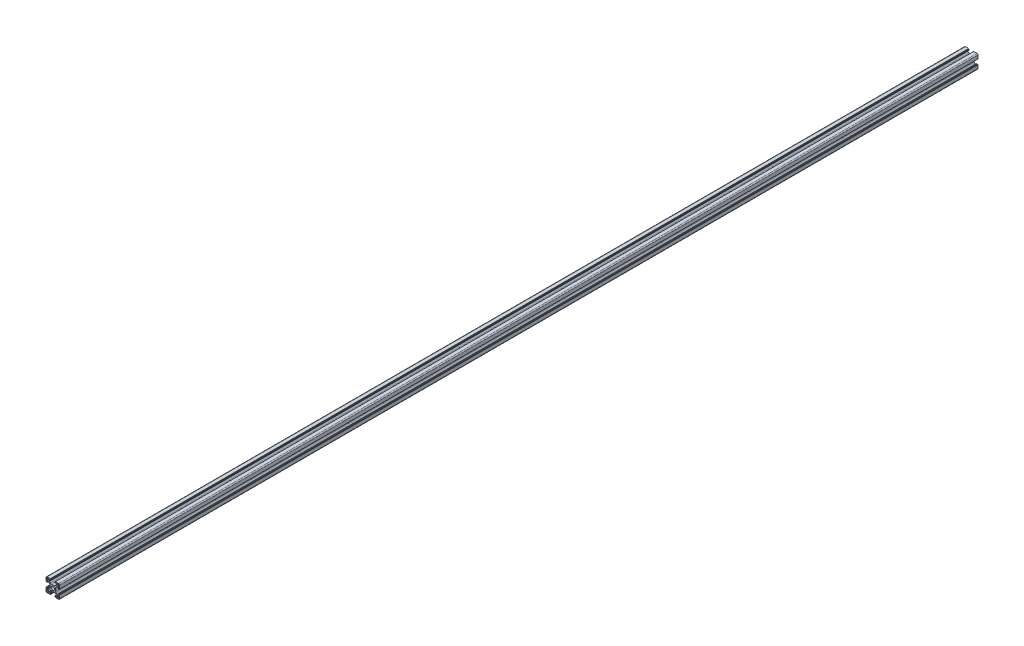
SolidWorks part; units mm, degrees
ref_plane "Спереди" through (0, 0, 0) normal (0, 0, 1) x (1, 0, 0)
ref_plane "Сверху" through (0, 0, 0) normal (0, 1, 0) x (1, 0, 0)
ref_plane "Справа" through (0, 0, 0) normal (1, 0, 0) x (0, 0, -1)
sketch "Эскиз1" plane through (0, 0, 0) normal (0, 0, 1) x (1, 0, 0)
  line L0 (-25.8933, 69.2728) -> (-28.8933, 66.2728) construction
  line L1 (-34.9933, 64.1728) -> (-33.0945, 64.1728)
  line L2 (-34.9933, 60.1728) -> (-24.9933, 70.1728) construction
  line L3 (-27.3933, 67.7728) -> (-28.8933, 69.2728) construction
  line L4 (-31.6803, 64.7586) -> (-30.3791, 66.0598)
  line L5 (-28.0933, 66.2728) -> (-26.6933, 66.2728)
  line L6 (-28.8933, 67.0728) -> (-28.8933, 68.4728)
  line L7 (-26.6933, 69.2728) -> (-28.0933, 69.2728)
  line L8 (-29.7933, 68.3728) -> (-29.7933, 67.474)
  line L9 (-31.2301, 68.246) -> (-30.7498, 68.7264)
  line L10 (-31.7933, 69.7219) -> (-31.2933, 69.7219)
  line L11 (-31.4069, 68.1728) -> (-31.6933, 68.1728)
  line L12 (-30.3962, 68.8728) -> (-30.2933, 68.8728)
  line L13 (-31.2933, 70.0228) -> (-31.2933, 69.7219)
  line L14 (-31.9433, 69.5719) -> (-31.9433, 68.4228)
  line L15 (-26.4933, 70.1728) -> (-31.1433, 70.1728)
  line L16 (-25.8933, 68.4728) -> (-25.8933, 67.0728)
  line L17 (-24.9933, 68.6728) -> (-24.9933, 64.0228)
  line L18 (-25.5943, 63.2228) -> (-26.7433, 63.2228)
  line L19 (-25.1433, 63.8728) -> (-25.4443, 63.8728)
  line L20 (-26.2933, 64.7699) -> (-26.2933, 64.8728)
  line L21 (-26.9933, 63.7592) -> (-26.9933, 63.4728)
  line L22 (-25.4443, 63.3728) -> (-25.4443, 63.8728)
  line L23 (-26.9201, 63.936) -> (-26.4398, 64.4164)
  line L24 (-26.7933, 65.3728) -> (-27.6921, 65.3728)
  line L25 (-30.4075, 63.4858) -> (-29.1063, 64.787)
  line L26 (-30.9933, 60.1728) -> (-30.9933, 62.0716)
  line L27 (-30.9933, 60.1728) -> (-30.9933, 58.274)
  line L28 (-30.4075, 56.8598) -> (-29.1063, 55.5586)
  line L29 (-28.8933, 53.2728) -> (-28.8933, 51.8728)
  line L30 (-28.0933, 54.0728) -> (-26.6933, 54.0728)
  line L31 (-25.8933, 51.8728) -> (-25.8933, 53.2728)
  line L32 (-26.7933, 54.9728) -> (-27.6921, 54.9728)
  line L33 (-26.9201, 56.4096) -> (-26.4398, 55.9292)
  line L34 (-25.4443, 56.9728) -> (-25.4443, 56.4728)
  line L35 (-26.9933, 56.5864) -> (-26.9933, 56.8728)
  line L36 (-26.2933, 55.5757) -> (-26.2933, 55.4728)
  line L37 (-25.1433, 56.4728) -> (-25.4443, 56.4728)
  line L38 (-25.5943, 57.1228) -> (-26.7433, 57.1228)
  line L39 (-24.9933, 51.6728) -> (-24.9933, 56.3228)
  line L40 (-26.6933, 51.0728) -> (-28.0933, 51.0728)
  line L41 (-26.4933, 50.1728) -> (-31.1433, 50.1728)
  line L42 (-31.9433, 50.7737) -> (-31.9433, 51.9228)
  line L43 (-31.2933, 50.3228) -> (-31.2933, 50.6237)
  line L44 (-30.3962, 51.4728) -> (-30.2933, 51.4728)
  line L45 (-31.4069, 52.1728) -> (-31.6933, 52.1728)
  line L46 (-31.7933, 50.6237) -> (-31.2933, 50.6237)
  line L47 (-31.2301, 52.0996) -> (-30.7498, 51.6192)
  line L48 (-29.7933, 51.9728) -> (-29.7933, 52.8716)
  line L49 (-31.6803, 55.587) -> (-30.3791, 54.2858)
  line L50 (-34.9933, 56.1728) -> (-33.0945, 56.1728)
  line L51 (-25.8933, 51.0728) -> (-28.8933, 54.0728) construction
  line L52 (-34.9933, 60.1728) -> (-24.9933, 50.1728) construction
  line L53 (-27.3933, 52.5728) -> (-25.8933, 54.0728) construction
  line L54 (-34.9933, 56.1728) -> (-36.8921, 56.1728)
  line L55 (-38.3063, 55.587) -> (-39.6075, 54.2858)
  line L56 (-41.8933, 54.0728) -> (-43.2933, 54.0728)
  line L57 (-41.0933, 53.2728) -> (-41.0933, 51.8728)
  line L58 (-43.2933, 51.0728) -> (-41.8933, 51.0728)
  line L59 (-40.1933, 51.9728) -> (-40.1933, 52.8716)
  line L60 (-38.7565, 52.0996) -> (-39.2369, 51.6192)
  line L61 (-38.1933, 50.6237) -> (-38.6933, 50.6237)
  line L62 (-38.5798, 52.1728) -> (-38.2933, 52.1728)
  line L63 (-39.5904, 51.4728) -> (-39.6933, 51.4728)
  line L64 (-38.6933, 50.3228) -> (-38.6933, 50.6237)
  line L65 (-38.0433, 50.7737) -> (-38.0433, 51.9228)
  line L66 (-43.4933, 50.1728) -> (-38.8433, 50.1728)
  line L67 (-44.0933, 51.8728) -> (-44.0933, 53.2728)
  line L68 (-44.9933, 51.6728) -> (-44.9933, 56.3228)
  line L69 (-44.3924, 57.1228) -> (-43.2433, 57.1228)
  line L70 (-44.8433, 56.4728) -> (-44.5424, 56.4728)
  line L71 (-43.6933, 55.5757) -> (-43.6933, 55.4728)
  line L72 (-42.9933, 56.5864) -> (-42.9933, 56.8728)
  line L73 (-44.5424, 56.9728) -> (-44.5424, 56.4728)
  line L74 (-43.0665, 56.4096) -> (-43.5469, 55.9292)
  line L75 (-43.1933, 54.9728) -> (-42.2945, 54.9728)
  line L76 (-39.5791, 56.8598) -> (-40.8803, 55.5586)
  line L77 (-38.9933, 60.1728) -> (-38.9933, 58.274)
  line L78 (-44.0933, 51.0728) -> (-41.0933, 54.0728) construction
  line L79 (-34.9933, 60.1728) -> (-44.9933, 50.1728) construction
  line L80 (-42.5933, 52.5728) -> (-41.0933, 51.0728) construction
  line L81 (-38.9933, 60.1728) -> (-38.9933, 62.0716)
  line L82 (-39.5791, 63.4858) -> (-40.8803, 64.787)
  line L83 (-41.0933, 67.0728) -> (-41.0933, 68.4728)
  line L84 (-41.8933, 66.2728) -> (-43.2933, 66.2728)
  line L85 (-44.0933, 68.4728) -> (-44.0933, 67.0728)
  line L86 (-43.1933, 65.3728) -> (-42.2945, 65.3728)
  line L87 (-43.0665, 63.936) -> (-43.5469, 64.4164)
  line L88 (-44.5424, 63.3728) -> (-44.5424, 63.8728)
  line L89 (-42.9933, 63.7592) -> (-42.9933, 63.4728)
  line L90 (-43.6933, 64.7699) -> (-43.6933, 64.8728)
  line L91 (-44.8433, 63.8728) -> (-44.5424, 63.8728)
  line L92 (-44.3924, 63.2228) -> (-43.2433, 63.2228)
  line L93 (-44.9933, 68.6728) -> (-44.9933, 64.0228)
  line L94 (-43.2933, 69.2728) -> (-41.8933, 69.2728)
  line L95 (-43.4933, 70.1728) -> (-38.8433, 70.1728)
  line L96 (-38.0433, 69.5719) -> (-38.0433, 68.4228)
  line L97 (-38.6933, 70.0228) -> (-38.6933, 69.7219)
  line L98 (-39.5904, 68.8728) -> (-39.6933, 68.8728)
  line L99 (-38.5798, 68.1728) -> (-38.2933, 68.1728)
  line L100 (-38.1933, 69.7219) -> (-38.6933, 69.7219)
  line L101 (-38.7565, 68.246) -> (-39.2369, 68.7264)
  line L102 (-40.1933, 68.3728) -> (-40.1933, 67.474)
  line L103 (-38.3063, 64.7586) -> (-39.6075, 66.0598)
  line L104 (-34.9933, 64.1728) -> (-36.8921, 64.1728)
  line L105 (-46.7574, 60.1728) -> (-23.489, 60.1728) construction
  line L106 (-44.0933, 69.2728) -> (-41.0933, 66.2728) construction
  line L107 (-34.9933, 48.0864) -> (-34.9933, 70.8917) construction
  line L108 (-34.9933, 60.1728) -> (-44.9933, 70.1728) construction
  line L109 (-42.5933, 67.7728) -> (-44.0933, 66.2728) construction
  arc A0 (-25.8933, 68.4728) -> (-26.6933, 69.2728) centre (-26.6933, 68.4728) ccw
  arc A1 (-28.0933, 69.2728) -> (-28.8933, 68.4728) centre (-28.0933, 68.4728) ccw
  arc A2 (-28.0933, 66.2728) -> (-28.8933, 67.0728) centre (-28.0933, 67.0728) cw
  arc A3 (-26.4933, 70.1728) -> (-24.9933, 68.6728) centre (-26.4933, 68.6728) cw
  arc A4 (-31.7933, 69.7219) -> (-31.9433, 69.5719) centre (-31.7933, 69.5719) ccw
  arc A5 (-31.1433, 70.1728) -> (-31.2933, 70.0228) centre (-31.1433, 70.0228) ccw
  arc A6 (-31.4069, 68.1728) -> (-31.2301, 68.246) centre (-31.4069, 68.4228) ccw
  arc A7 (-31.6933, 68.1728) -> (-31.9433, 68.4228) centre (-31.6933, 68.4228) cw
  arc A8 (-30.7498, 68.7264) -> (-30.3962, 68.8728) centre (-30.3962, 68.3728) cw
  arc A9 (-30.2933, 68.8728) -> (-29.7933, 68.3728) centre (-30.2933, 68.3728) cw
  arc A10 (-32.4933, 60.1728) -> (-34.9933, 62.6728) centre (-34.9933, 60.1728) ccw
  arc A11 (-33.0945, 64.1728) -> (-31.6803, 64.7586) centre (-33.0945, 66.1728) ccw
  arc A12 (-29.7933, 67.474) -> (-30.3791, 66.0598) centre (-31.7933, 67.474) cw
  arc A13 (-25.8933, 67.0728) -> (-26.6933, 66.2728) centre (-26.6933, 67.0728) cw
  arc A14 (-26.2933, 64.8728) -> (-26.7933, 65.3728) centre (-26.7933, 64.8728) ccw
  arc A15 (-26.4398, 64.4164) -> (-26.2933, 64.7699) centre (-26.7933, 64.7699) ccw
  arc A16 (-26.9933, 63.4728) -> (-26.7433, 63.2228) centre (-26.7433, 63.4728) ccw
  arc A17 (-26.9933, 63.7592) -> (-26.9201, 63.936) centre (-26.7433, 63.7592) cw
  arc A18 (-24.9933, 64.0228) -> (-25.1433, 63.8728) centre (-25.1433, 64.0228) cw
  arc A19 (-25.4443, 63.3728) -> (-25.5943, 63.2228) centre (-25.5943, 63.3728) cw
  arc A20 (-27.6921, 65.3728) -> (-29.1063, 64.787) centre (-27.6921, 63.3728) ccw
  arc A21 (-30.9933, 62.0716) -> (-30.4075, 63.4858) centre (-28.9933, 62.0716) cw
  arc A22 (-26.6933, 51.0728) -> (-25.8933, 51.8728) centre (-26.6933, 51.8728) ccw
  arc A23 (-25.8933, 53.2728) -> (-26.6933, 54.0728) centre (-26.6933, 53.2728) ccw
  arc A24 (-28.8933, 53.2728) -> (-28.0933, 54.0728) centre (-28.0933, 53.2728) cw
  arc A25 (-24.9933, 51.6728) -> (-26.4933, 50.1728) centre (-26.4933, 51.6728) cw
  arc A26 (-25.4443, 56.9728) -> (-25.5943, 57.1228) centre (-25.5943, 56.9728) ccw
  arc A27 (-24.9933, 56.3228) -> (-25.1433, 56.4728) centre (-25.1433, 56.3228) ccw
  arc A28 (-26.9933, 56.5864) -> (-26.9201, 56.4096) centre (-26.7433, 56.5864) ccw
  arc A29 (-26.9933, 56.8728) -> (-26.7433, 57.1228) centre (-26.7433, 56.8728) cw
  arc A30 (-26.4398, 55.9292) -> (-26.2933, 55.5757) centre (-26.7933, 55.5757) cw
  arc A31 (-26.2933, 55.4728) -> (-26.7933, 54.9728) centre (-26.7933, 55.4728) cw
  arc A32 (-34.9933, 57.6728) -> (-32.4933, 60.1728) centre (-34.9933, 60.1728) ccw
  arc A33 (-30.9933, 58.274) -> (-30.4075, 56.8598) centre (-28.9933, 58.274) ccw
  arc A34 (-27.6921, 54.9728) -> (-29.1063, 55.5586) centre (-27.6921, 56.9728) cw
  arc A35 (-28.0933, 51.0728) -> (-28.8933, 51.8728) centre (-28.0933, 51.8728) cw
  arc A36 (-30.2933, 51.4728) -> (-29.7933, 51.9728) centre (-30.2933, 51.9728) ccw
  arc A37 (-30.7498, 51.6192) -> (-30.3962, 51.4728) centre (-30.3962, 51.9728) ccw
  arc A38 (-31.6933, 52.1728) -> (-31.9433, 51.9228) centre (-31.6933, 51.9228) ccw
  arc A39 (-31.4069, 52.1728) -> (-31.2301, 52.0996) centre (-31.4069, 51.9228) cw
  arc A40 (-31.1433, 50.1728) -> (-31.2933, 50.3228) centre (-31.1433, 50.3228) cw
  arc A41 (-31.7933, 50.6237) -> (-31.9433, 50.7737) centre (-31.7933, 50.7737) cw
  arc A42 (-29.7933, 52.8716) -> (-30.3791, 54.2858) centre (-31.7933, 52.8716) ccw
  arc A43 (-33.0945, 56.1728) -> (-31.6803, 55.587) centre (-33.0945, 54.1728) cw
  arc A44 (-44.0933, 51.8728) -> (-43.2933, 51.0728) centre (-43.2933, 51.8728) ccw
  arc A45 (-41.8933, 51.0728) -> (-41.0933, 51.8728) centre (-41.8933, 51.8728) ccw
  arc A46 (-41.8933, 54.0728) -> (-41.0933, 53.2728) centre (-41.8933, 53.2728) cw
  arc A47 (-43.4933, 50.1728) -> (-44.9933, 51.6728) centre (-43.4933, 51.6728) cw
  arc A48 (-38.1933, 50.6237) -> (-38.0433, 50.7737) centre (-38.1933, 50.7737) ccw
  arc A49 (-38.8433, 50.1728) -> (-38.6933, 50.3228) centre (-38.8433, 50.3228) ccw
  arc A50 (-38.5798, 52.1728) -> (-38.7565, 52.0996) centre (-38.5798, 51.9228) ccw
  arc A51 (-38.2933, 52.1728) -> (-38.0433, 51.9228) centre (-38.2933, 51.9228) cw
  arc A52 (-39.2369, 51.6192) -> (-39.5904, 51.4728) centre (-39.5904, 51.9728) cw
  arc A53 (-39.6933, 51.4728) -> (-40.1933, 51.9728) centre (-39.6933, 51.9728) cw
  arc A54 (-37.4933, 60.1728) -> (-34.9933, 57.6728) centre (-34.9933, 60.1728) ccw
  arc A55 (-36.8921, 56.1728) -> (-38.3063, 55.587) centre (-36.8921, 54.1728) ccw
  arc A56 (-40.1933, 52.8716) -> (-39.6075, 54.2858) centre (-38.1933, 52.8716) cw
  arc A57 (-44.0933, 53.2728) -> (-43.2933, 54.0728) centre (-43.2933, 53.2728) cw
  arc A58 (-43.6933, 55.4728) -> (-43.1933, 54.9728) centre (-43.1933, 55.4728) ccw
  arc A59 (-43.5469, 55.9292) -> (-43.6933, 55.5757) centre (-43.1933, 55.5757) ccw
  arc A60 (-42.9933, 56.8728) -> (-43.2433, 57.1228) centre (-43.2433, 56.8728) ccw
  arc A61 (-42.9933, 56.5864) -> (-43.0665, 56.4096) centre (-43.2433, 56.5864) cw
  arc A62 (-44.9933, 56.3228) -> (-44.8433, 56.4728) centre (-44.8433, 56.3228) cw
  arc A63 (-44.5424, 56.9728) -> (-44.3924, 57.1228) centre (-44.3924, 56.9728) cw
  arc A64 (-42.2945, 54.9728) -> (-40.8803, 55.5586) centre (-42.2945, 56.9728) ccw
  arc A65 (-38.9933, 58.274) -> (-39.5791, 56.8598) centre (-40.9933, 58.274) cw
  arc A66 (-43.2933, 69.2728) -> (-44.0933, 68.4728) centre (-43.2933, 68.4728) ccw
  arc A67 (-44.0933, 67.0728) -> (-43.2933, 66.2728) centre (-43.2933, 67.0728) ccw
  arc A68 (-41.0933, 67.0728) -> (-41.8933, 66.2728) centre (-41.8933, 67.0728) cw
  arc A69 (-44.9933, 68.6728) -> (-43.4933, 70.1728) centre (-43.4933, 68.6728) cw
  arc A70 (-44.5424, 63.3728) -> (-44.3924, 63.2228) centre (-44.3924, 63.3728) ccw
  arc A71 (-44.9933, 64.0228) -> (-44.8433, 63.8728) centre (-44.8433, 64.0228) ccw
  arc A72 (-42.9933, 63.7592) -> (-43.0665, 63.936) centre (-43.2433, 63.7592) ccw
  arc A73 (-42.9933, 63.4728) -> (-43.2433, 63.2228) centre (-43.2433, 63.4728) cw
  arc A74 (-43.5469, 64.4164) -> (-43.6933, 64.7699) centre (-43.1933, 64.7699) cw
  arc A75 (-43.6933, 64.8728) -> (-43.1933, 65.3728) centre (-43.1933, 64.8728) cw
  arc A76 (-34.9933, 62.6728) -> (-37.4933, 60.1728) centre (-34.9933, 60.1728) ccw
  arc A77 (-38.9933, 62.0716) -> (-39.5791, 63.4858) centre (-40.9933, 62.0716) ccw
  arc A78 (-42.2945, 65.3728) -> (-40.8803, 64.787) centre (-42.2945, 63.3728) cw
  arc A79 (-41.8933, 69.2728) -> (-41.0933, 68.4728) centre (-41.8933, 68.4728) cw
  arc A80 (-39.6933, 68.8728) -> (-40.1933, 68.3728) centre (-39.6933, 68.3728) ccw
  arc A81 (-39.2369, 68.7264) -> (-39.5904, 68.8728) centre (-39.5904, 68.3728) ccw
  arc A82 (-38.2933, 68.1728) -> (-38.0433, 68.4228) centre (-38.2933, 68.4228) ccw
  arc A83 (-38.5798, 68.1728) -> (-38.7565, 68.246) centre (-38.5798, 68.4228) cw
  arc A84 (-38.8433, 70.1728) -> (-38.6933, 70.0228) centre (-38.8433, 70.0228) cw
  arc A85 (-38.1933, 69.7219) -> (-38.0433, 69.5719) centre (-38.1933, 69.5719) cw
  arc A86 (-40.1933, 67.474) -> (-39.6075, 66.0598) centre (-38.1933, 67.474) ccw
  arc A87 (-36.8921, 64.1728) -> (-38.3063, 64.7586) centre (-36.8921, 66.1728) cw
  point P0 (-34.9933, 60.1728)
  point P9 (-34.9933, 60.1728)
  point P40 (-26.2933, 63.8728)
  point P93 (-31.2933, 51.4728)
  point P144 (-31.2933, 68.8728)
  point P152 (-26.2933, 56.4728)
  point P153 (-34.9933, 56.2485)
  point P154 (-34.9933, 60.1728)
  point P189 (-43.6933, 56.4728)
  point P228 (-38.6933, 51.4728)
  point P229 (-38.9176, 60.1728)
  point P230 (-34.9933, 60.1728)
  point P268 (-38.6933, 68.8728)
  point P273 (-31.0691, 60.1728)
  point P306 (-43.6933, 63.8728)
  point P307 (-34.9933, 64.0971)
  point P309 (-34.9933, 60.1728)
  dimension "D3" = 5
  dimension "D6" = 2
  dimension "D1" = 2
  dimension "D2" = 6
  dimension "D4" = 4
  dimension "D5" = 0.9
extrude "Бобышка-Вытянуть1" add sketch "Эскиз1" along normal blind 1350
